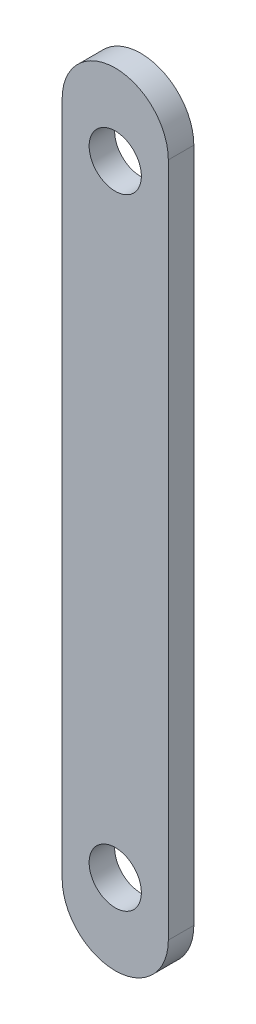
SolidWorks part; units mm, degrees
ref_plane "Ön Düzlem" through (0, 0, 0) normal (0, 0, 1) x (1, 0, 0)
ref_plane "Üst Düzlem" through (0, 0, 0) normal (0, 1, 0) x (1, 0, 0)
ref_plane "Sağ Düzlem" through (0, 0, 0) normal (1, 0, 0) x (0, 0, -1)
sketch "Çizim1" plane through (0, 0, 0) normal (0, 0, 1) x (1, 0, 0)
  line L0 (0, -49) -> (0, 49) construction
  line L1 (-7.6977, -49) -> (-7.6977, 49)
  line L2 (7.6977, -49) -> (7.6977, 49)
  line L3 (0, 0) -> (50000, 0) construction
  arc A0 (-7.6977, -49) -> (7.6977, -49) centre (0, -49) ccw
  arc A1 (7.6977, 49) -> (-7.6977, 49) centre (0, 49) ccw
  circle A2 centre (0, -45) radius 3.788
  circle A3 centre (0, 45) radius 3.788
  point P2 (0, 0)
  dimension "D1" = 98
  dimension "D2" = 45
extrude "Yükseklik-Ekstrüzyon1" add sketch "Çizim1" along normal blind 3.7
